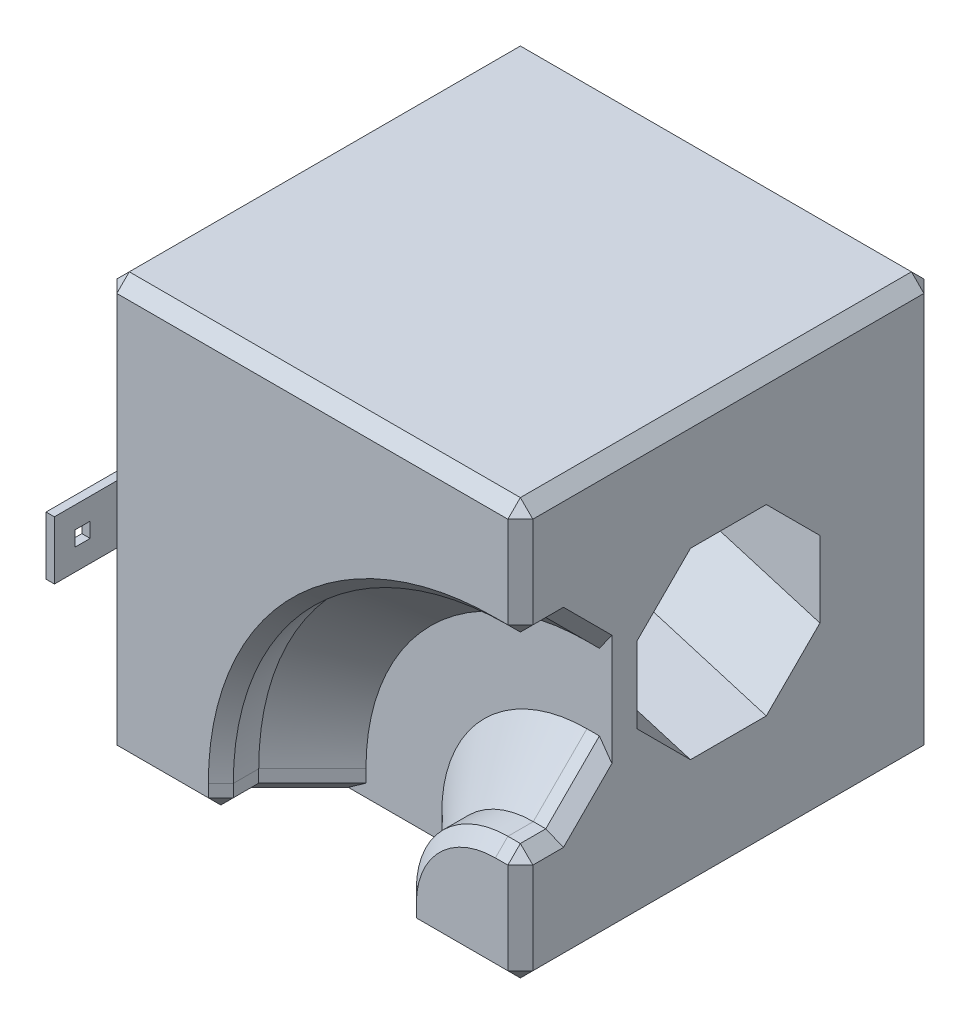
SolidWorks part; units mm, degrees
ref_plane "Front" through (0, 0, 0) normal (0, 0, 1) x (1, 0, 0)
ref_plane "Top" through (0, 0, 0) normal (0, 1, 0) x (1, 0, 0)
ref_plane "Right" through (0, 0, 0) normal (1, 0, 0) x (0, 0, -1)
sketch "Sketch1" plane through (0, 0, 0) normal (0, 0, 1) x (1, 0, 0)
  line L1 (0, 0) -> (50, 0)
  line L2 (0, 0) -> (0, 50)
  line L3 (0, 50) -> (50, 50)
  line L4 (50, 0) -> (50, 50)
  dimension "D1" = 50
extrude "Boss-Extrude1" add sketch "Sketch1" along normal blind 50
sketch "Sketch2" plane through (50, 0, 0) normal (-1, 0, 0) x (0, 0, 1)
  line L0 (25, 25) -> (25, 50) construction
  line L1 (50, 25) -> (25, 25) construction
  line L2 (50, 50) -> (50, 0) construction
  line L7 (50, 50) -> (0, 50) construction
  line L10 (14, 36) -> (36, 36) construction
  line L11 (14, 36) -> (14, 14) construction
  line L12 (14, 14) -> (36, 14) construction
  line L13 (36, 36) -> (36, 14) construction
  line L14 (36, 29.5563) -> (29.5563, 36)
  line L15 (14, 36) -> (36, 14) construction
  line L16 (29.5563, 36) -> (20.4437, 36)
  line L17 (14, 14) -> (36, 36) construction
  line L26 (20.4437, 36) -> (14, 29.5563)
  line L27 (14, 29.5563) -> (14, 20.4437)
  line L28 (14, 20.4437) -> (20.4437, 14)
  line L29 (20.4437, 14) -> (29.5563, 14)
  line L30 (29.5563, 14) -> (36, 20.4437)
  line L31 (36, 20.4437) -> (36, 29.5563)
  circle A1 centre (25, 25) radius 11 construction
  point P5 (25, 25)
  dimension "D1" = 22
sketch "Sketch3" plane through (0, 0, 0) normal (0, -1, 0) x (1, 0, 0)
  line L0 (0, 50) -> (50, 50) construction
  line L7 (14, 61) -> (36, 61) construction
  line L8 (14, 61) -> (14, 39) construction
  line L9 (14, 39) -> (36, 39) construction
  line L10 (36, 61) -> (36, 39) construction
  line L11 (14, 61) -> (36, 39) construction
  line L12 (14, 39) -> (36, 61) construction
  line L16 (29.5563, 39) -> (36, 45.4437)
  line L17 (36, 45.4437) -> (36, 54.5563)
  line L18 (36, 54.5563) -> (29.5563, 61)
  line L19 (29.5563, 61) -> (20.4437, 61)
  line L20 (20.4437, 61) -> (14, 54.5563)
  line L21 (14, 54.5563) -> (14, 45.4437)
  line L22 (14, 45.4437) -> (20.4437, 39)
  line L23 (20.4437, 39) -> (29.5563, 39)
  circle A0 centre (25, 50) radius 11 construction
  point P5 (25, 50)
  dimension "D1" = 22
sketch "Sketch4" plane through (0, 0, 50) normal (0, 0, 1) x (1, 0, 0)
  line L0 (25, 0) -> (25, 3)
  line L1 (47, 25) -> (50, 25)
  line L2 (50, 0) -> (50, 50) construction
  arc A0 (25, 3) -> (47, 25) centre (47, 3) cw
  dimension "D1" = 22
sweep "Cut-Sweep1" cut profiles "Sketch3" path "Sketch4"
sketch "Sketch5" plane through (0, 0, 0) normal (-1, 0, 0) x (0, 0, 1)
  line L0 (29.5563, 36) -> (20.4437, 36) construction
  line L1 (18.0563, 36) -> (8.9437, 36)
  line L2 (8.9437, 36) -> (2.5, 29.5563)
  line L3 (2.5, 29.5563) -> (2.5, 20.4437)
  line L4 (2.5, 20.4437) -> (8.9437, 14)
  line L5 (8.9437, 14) -> (18.0563, 14)
  line L6 (18.0563, 14) -> (24.5, 20.4437)
  line L7 (24.5, 20.4437) -> (24.5, 29.5563)
  line L8 (24.5, 29.5563) -> (18.0563, 36)
  line L10 (25, 25) -> (0, 25) construction
  line L11 (14, 36) -> (36, 14) construction
  line L12 (0, 50) -> (0, 0) construction
  circle A0 centre (13.5, 25) radius 11 construction
  dimension "D1" = 2.5
loft "Cut-Loft1" cut profiles "Sketch5", "Sketch2"
chamfer "Chamfer1" distance 1.5 angle 45 28 edges at (48.5, 36, 50) (14, 1.5, 50) (23.6655, 26.3345, 50) (36, 1.5, 50) (39.2218, 10.7782, 50) (25, 50, 0) (50, 25, 0) (50, 50, 25) (50, 17.2218, 42.2218) (32.7782, 0, 42.2218) (36, 0, 47.7218) (43, 0, 50) (50, 14, 47.7218) (48.5, 14, 50) (50, 7, 50) (50, 0, 25) (25, 0, 0) (0, 25, 0) (0, 0, 25) (17.2218, 0, 42.2218) (14, 0, 47.7218) (50, 32.7782, 42.2218) (50, 36, 47.7218) (50, 43, 50) (7, 0, 50) (0, 50, 25) (25, 50, 50) (0, 25, 50)
sketch "Sketch6" plane through (0, 0, 50) normal (0, 0, 1) x (1, 0, 0)
  line L0 (0, 1.5) -> (0, 48.5) construction
  line L1 (0, 28.5) -> (1, 28.5)
  line L2 (0, 28.5) -> (0, 21.5)
  line L3 (0, 21.5) -> (1, 21.5)
  line L4 (1, 28.5) -> (1, 21.5)
  point P6 (0, 25)
  dimension "D1" = 7
  dimension "D2" = 1
extrude "Boss-Extrude2" add sketch "Sketch6" along normal blind 7 and the other way blind 10
sketch "Sketch7" plane through (1, 0, 0) normal (1, 0, 0) x (0, 0, -1)
  line L0 (-54.5, 25) -> (-57, 25) construction
  line L1 (-54.5, 24.1) -> (-52.7, 24.1)
  line L2 (-54.5, 24.1) -> (-54.5, 25.9)
  line L3 (-54.5, 25.9) -> (-52.7, 25.9)
  line L4 (-52.7, 24.1) -> (-52.7, 25.9)
  line L5 (-57, 21.5) -> (-57, 28.5) construction
  dimension "D1" = 2.5
  dimension "D2" = 1.8
extrude "Cut-Extrude1" cut sketch "Sketch7" against normal blind 7
